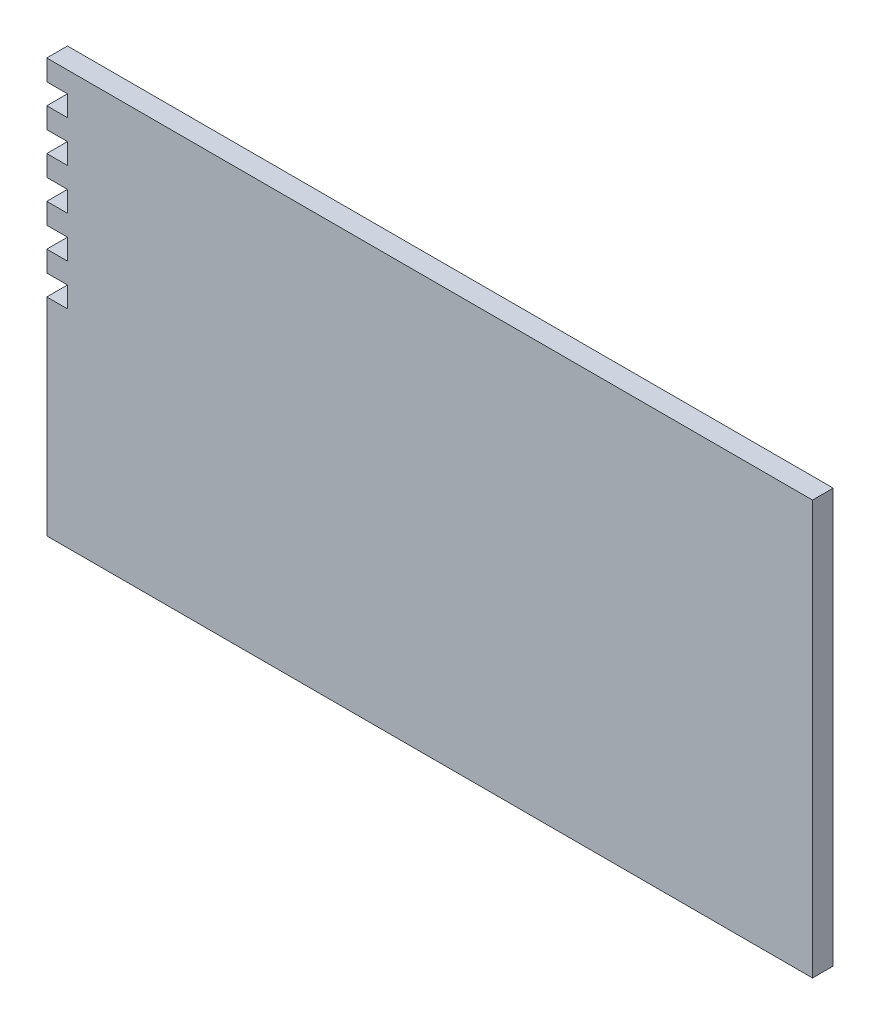
SolidWorks part; units mm, degrees
ref_plane "Plano frontal" through (0, 0, 0) normal (0, 0, 1) x (1, 0, 0)
ref_plane "Plano superior" through (0, 0, 0) normal (0, 1, 0) x (1, 0, 0)
ref_plane "Plano direito" through (0, 0, 0) normal (1, 0, 0) x (0, 0, -1)
sketch "Esboço1" plane through (0, 0, 0) normal (0, 0, 1) x (1, 0, 0)
  line L1 (117, -63) -> (-105, -63)
  line L2 (117, -63) -> (117, 57)
  line L3 (117, 57) -> (-105, 57)
  line L4 (-105, -63) -> (-105, 57)
  point P0 (0, 0)
  dimension "D1" = 222
  dimension "D2" = 120
extrude "Ressalto-extrusão1" add sketch "Esboço1" along normal blind 6
sketch "Esboço3" plane through (0, 0, 6) normal (0, 0, 1) x (1, 0, 0)
  line L0 (0, 0) -> (-105, 0) construction
  line L1 (-105, 57) -> (-105, -63) construction
  line L2 (-105, -3) -> (-105, 3)
  line L6 (-105, 3) -> (-99, 3)
  line L7 (-99, 3) -> (-99, -3)
  line L8 (-99, -3) -> (-105, -3)
  point P8 (-105, 0)
  dimension "D1" = 6
  dimension "D3" = 6
extrude "Corte-extrusão1" cut sketch "Esboço3" against normal through all
pattern_linear "Padrão linear2" count 5 spacing 12 along (0, 1, 0) of "Corte-extrusão1"
